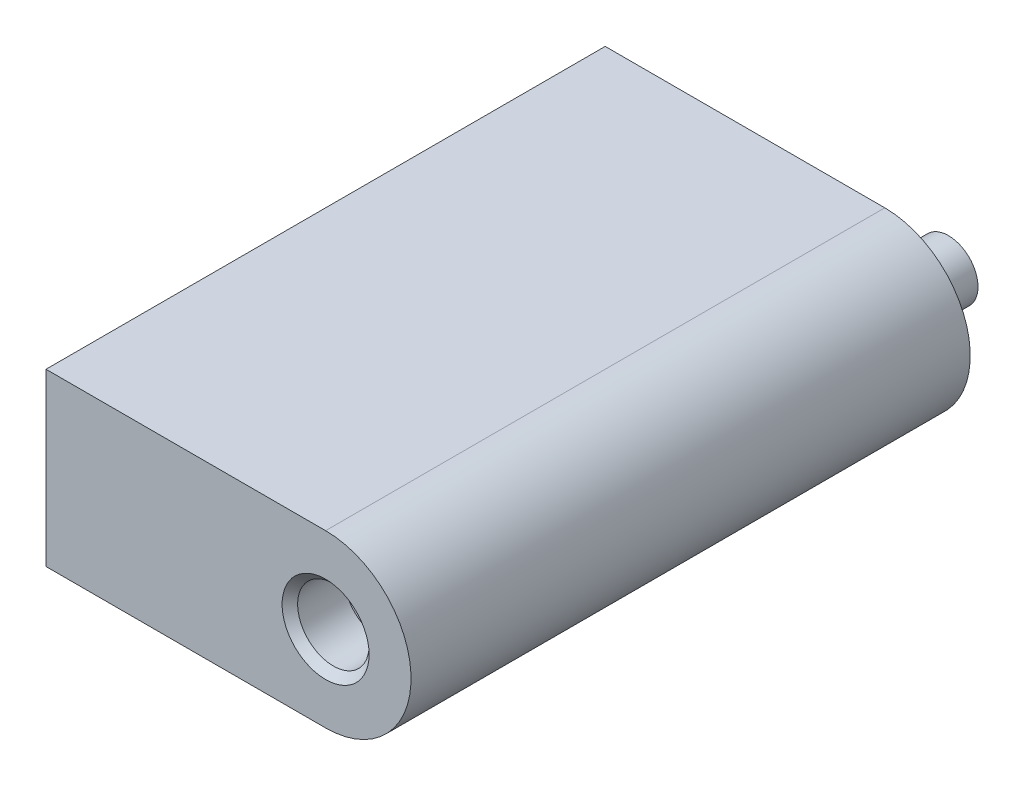
SolidWorks part; units mm, degrees
ref_plane "Plan de face" through (0, 0, 0) normal (0, 0, 1) x (1, 0, 0)
ref_plane "Plan de dessus" through (0, 0, 0) normal (0, 1, 0) x (1, 0, 0)
ref_plane "Plan de droite" through (0, 0, 0) normal (1, 0, 0) x (0, 0, -1)
sketch "Esquisse1" plane through (0, 0, 0) normal (0, 0, 1) x (1, 0, 0)
  line L0 (0, 5.5) -> (-18, 5.5)
  line L1 (-18, 5.5) -> (-18, -5.5)
  line L2 (-18, -5.5) -> (0, -5.5)
  arc A0 (0, -5.5) -> (0, 5.5) centre (0, 0) ccw
  dimension "D1" = 18
  dimension "D2" = 5.5
extrude "Boss.-Extru.1" add sketch "Esquisse1" along normal blind 36
sketch "Esquisse2" plane through (-18, 0, 0) normal (-1, 0, 0) x (0, 0, 1)
  line L1 (31.5475, -4.5) -> (4.5475, -4.5)
  line L2 (31.5475, -4.5) -> (31.5475, 4.5)
  line L3 (31.5475, 4.5) -> (4.5475, 4.5)
  line L4 (4.5475, -4.5) -> (4.5475, 4.5)
  line L5 (31.5475, -4.5) -> (4.5475, 4.5) construction
  line L6 (31.5475, 4.5) -> (4.5475, -4.5) construction
  point P0 (18.0475, 0)
  dimension "D1" = 9
  dimension "D2" = 27
extrude "Enlèv. mat.-Extru.1" cut sketch "Esquisse2" against normal blind 9
sketch "Esquisse3" plane through (0, 0, 36) normal (0, 0, 1) x (1, 0, 0)
  circle A0 centre (0, 0) radius 2.3
  dimension "D1" = 4.6
extrude "Enlèv. mat.-Extru.2" cut sketch "Esquisse3" against normal blind 3.5
sketch "Esquisse4" plane through (0, 0, 0) normal (0, 0, -1) x (-1, 0, 0)
  circle A0 centre (0, 0) radius 1.9
  dimension "D1" = 3.8
extrude "Boss.-Extru.2" add sketch "Esquisse4" along normal blind 4.1
fillet "Congé1" radius 1 1 edges at (1.9, 0, 0)
chamfer "Chanfrein1" distance 0.5 angle 45 1 edges at (2.3, 0, 36)
chamfer "Chanfrein2" distance 0.5 angle 45 4 edges at (-18, 0, 4.5475) (-18, -4.5, 18.0475) (-18, 4.5, 18.0475) (-18, 0, 31.5475)
